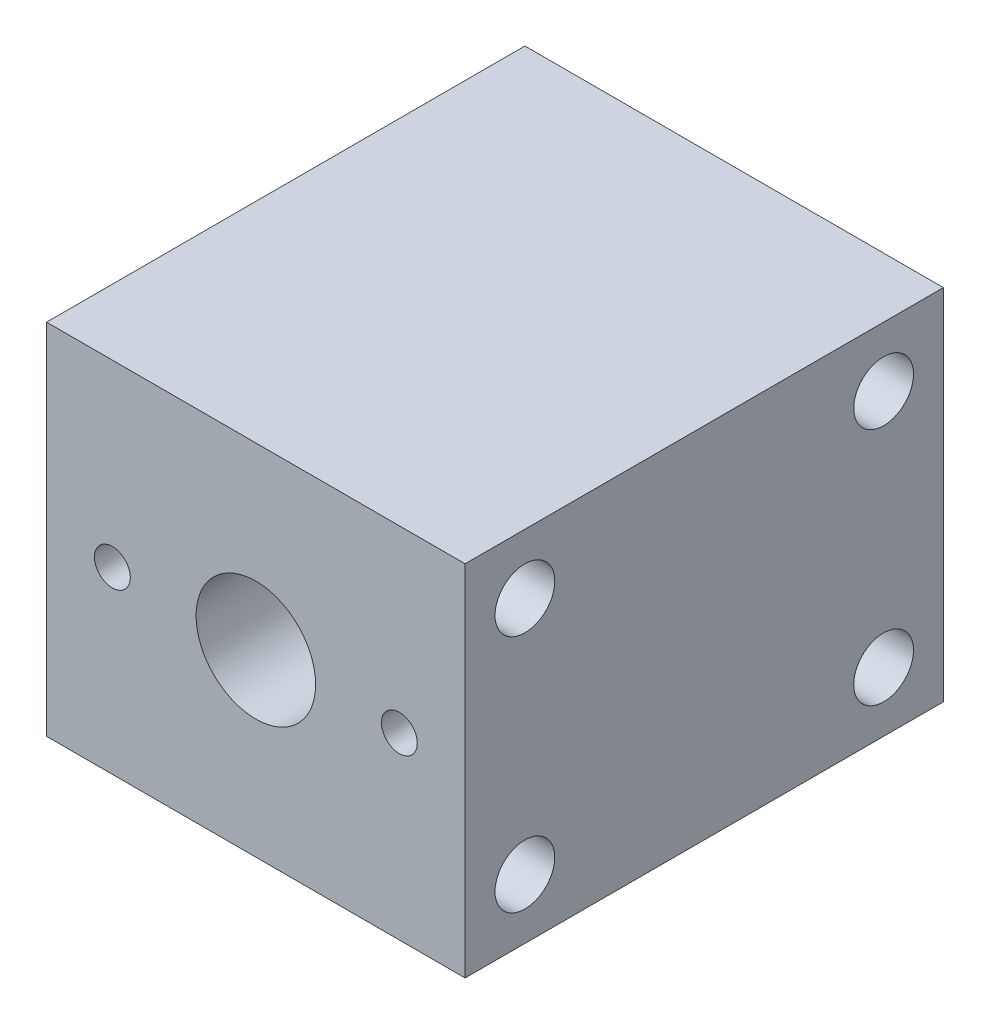
SolidWorks part; units mm, degrees
material "Nylon 101"
ref_plane "Front Plane" through (0, 0, 0) normal (0, 0, 1) x (1, 0, 0)
ref_plane "Top Plane" through (0, 0, 0) normal (0, 1, 0) x (1, 0, 0)
ref_plane "Right Plane" through (0, 0, 0) normal (1, 0, 0) x (0, 0, -1)
sketch "Sketch1" plane through (0, 0, 0) normal (0, 0, 1) x (1, 0, 0)
  line L1 (-17.5, -15) -> (17.5, -15)
  line L2 (-17.5, -15) -> (-17.5, 15)
  line L3 (-17.5, 15) -> (17.5, 15)
  line L4 (17.5, -15) -> (17.5, 15)
  line L5 (-17.5, -15) -> (17.5, 15) construction
  line L6 (-17.5, 15) -> (17.5, -15) construction
  circle A0 centre (0, 0) radius 5
  dimension "D1" = 10
  dimension "D2" = 35
  dimension "D3" = 30
extrude "Boss-Extrude1" add sketch "Sketch1" along normal mid plane 40
sketch "Sketch2" plane through (17.5, 0, 0) normal (1, 0, 0) x (0, 0, -1)
  line L0 (0, 0) -> (-12.9049, 0) construction
  circle A0 centre (-15, 10) radius 2.5
  circle A1 centre (15, 10) radius 2.5
  circle A2 centre (15, -10) radius 2.5
  circle A3 centre (-15, -10) radius 2.5
  dimension "D3" = 5
  dimension "D1" = 30
  dimension "D2" = 10
  dimension "D4" = 15
extrude "Cut-Extrude1" cut sketch "Sketch2" against normal through all
sketch "Sketch3" plane through (0, 0, 20) normal (0, 0, 1) x (1, 0, 0)
  circle A0 centre (12, 0) radius 1.5
  circle A1 centre (-12, 0) radius 1.5
  dimension "D1" = 3
  dimension "D2" = 12
  dimension "D3" = 12
extrude "Cut-Extrude2" cut sketch "Sketch3" against normal through all
